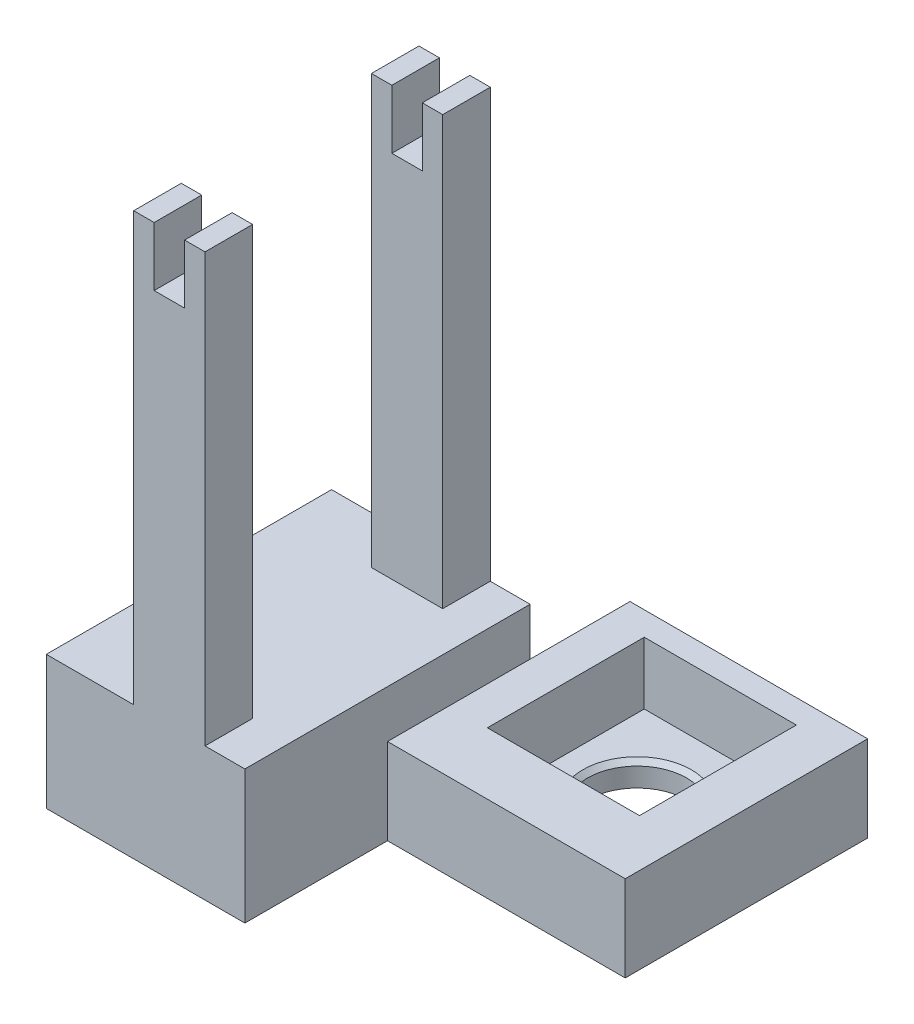
SolidWorks part; units mm, degrees
ref_plane "Front Plane" through (0, 0, 0) normal (0, 0, 1) x (1, 0, 0)
ref_plane "Top Plane" through (0, 0, 0) normal (0, 1, 0) x (1, 0, 0)
ref_plane "Right Plane" through (0, 0, 0) normal (1, 0, 0) x (0, 0, -1)
sketch "Sketch2" plane through (0, 0, 0) normal (0, 1, 0) x (1, 0, 0)
  line L1 (-25.885, -30) -> (15.885, -30)
  line L2 (-25.885, -30) -> (-25.885, 30)
  line L3 (-25.885, 30) -> (15.885, 30)
  line L4 (15.885, -30) -> (15.885, 30)
  point P0 (0, 0)
  point P6 (-25.885, 0)
  dimension "D1" = 41.77
  dimension "D2" = 60
  dimension "D3" = 25.885
extrude "Boss-Extrude1" add sketch "Sketch2" along normal blind 28.08
ref_plane "Plane1" [suppressed] through (0, 85, 0) normal (0, 1, 0) x (1, 0, 0)
sketch "Sketch3" [suppressed] plane through (0, 10, 0) normal (0, 1, 0) x (1, 0, 0)
  line L2 (-17.885, -27) -> (-17.885, -20)
  line L3 (-20.885, -20) -> (-17.885, -20)
  line L4 (-20.885, -30) -> (20.885, -30) construction
  line L5 (-17.885, -27) -> (-10.885, -27)
  line L6 (-20.885, -20) -> (-20.885, -30)
  line L7 (-10.885, -27) -> (-10.885, -30)
  line L8 (-20.885, -30) -> (-10.885, -30)
  line L9 (0, 30) -> (0, -30) construction
  line L10 (20.885, 30) -> (-20.885, 30) construction
  line L11 (-20.885, 0) -> (20.885, 0) construction
  line L12 (-20.885, 30) -> (-20.885, -30) construction
  line L13 (20.885, -30) -> (20.885, 30) construction
  line L14 (-17.885, -27) -> (-20.885, -27) construction
  line L15 (-17.885, -27) -> (-17.885, -30) construction
  line L16 (-20.885, 20) -> (-20.885, 30)
  line L17 (-20.885, 30) -> (-10.885, 30)
  line L18 (-10.885, 27) -> (-10.885, 30)
  line L19 (-17.885, 27) -> (-10.885, 27)
  line L20 (-17.885, 27) -> (-17.885, 20)
  line L21 (-20.885, 20) -> (-17.885, 20)
  line L22 (20.885, -20) -> (20.885, -30)
  line L23 (20.885, -30) -> (10.885, -30)
  line L24 (10.885, -27) -> (10.885, -30)
  line L25 (17.885, -27) -> (10.885, -27)
  line L26 (17.885, -27) -> (17.885, -20)
  line L27 (20.885, -20) -> (17.885, -20)
  line L28 (20.885, 20) -> (17.885, 20)
  line L29 (17.885, 27) -> (17.885, 20)
  line L30 (17.885, 27) -> (10.885, 27)
  line L31 (10.885, 27) -> (10.885, 30)
  line L32 (20.885, 30) -> (10.885, 30)
  line L33 (20.885, 20) -> (20.885, 30)
  dimension "D1" = 10
  dimension "D2" = 3
  dimension "D4" = 10
  dimension "D5" = 3
extrude "Boss-Extrude2" [suppressed] add sketch "Sketch3" along normal up to surface (75 mm away)
sketch "Sketch4" [suppressed] plane through (0, 0, 0) normal (0, -1, 0) x (1, 0, 0)
  line L0 (20.885, -30) -> (20.885, -5)
  line L1 (20.885, -30) -> (60.885, -30)
  line L2 (20.885, -5) -> (60.885, -5)
  line L3 (60.885, -30) -> (60.885, -5)
  line L4 (20.885, 30) -> (20.885, -30) construction
  dimension "D1" = 40
  dimension "D2" = 25
extrude "Boss-Extrude3" [suppressed] add sketch "Sketch4" against normal blind 10
sketch "Sketch6" plane through (0, 28.08, 0) normal (0, 1, 0) x (1, 0, 0)
  line L0 (-25.885, -30) -> (15.885, -30) construction
  line L1 (-7.5, -30) -> (7.5, -30)
  line L2 (-7.5, -30) -> (-7.5, -20)
  line L3 (-7.5, -20) -> (7.5, -20)
  line L4 (7.5, -30) -> (7.5, -20)
  line L5 (15.885, 30) -> (-25.885, 30) construction
  line L6 (-7.5, 30) -> (7.5, 30)
  line L7 (-7.5, 30) -> (-7.5, 20)
  line L8 (-7.5, 20) -> (7.5, 20)
  line L9 (7.5, 30) -> (7.5, 20)
  point P6 (0, -20)
  point P14 (0, 20)
  dimension "D1" = 10
  dimension "D2" = 15
extrude "Boss-Extrude4" add sketch "Sketch6" along normal blind 90
sketch "Sketch7" plane through (0, 0, -30) normal (0, 0, -1) x (-1, 0, 0)
  line L0 (-7.5, 118.08) -> (7.5, 118.08) construction
  line L1 (-3.2, 118.08) -> (3.2, 118.08)
  line L2 (-3.2, 118.08) -> (-3.2, 105.68)
  line L3 (-3.2, 105.68) -> (3.2, 105.68)
  line L4 (3.2, 118.08) -> (3.2, 105.68)
  point P6 (0, 105.68)
  dimension "D1" = 6.4
  dimension "D2" = 12.4
extrude "Cut-Extrude1" cut sketch "Sketch7" against normal through all
sketch "Sketch8" plane through (15.885, 0, 0) normal (1, 0, 0) x (0, 0, -1)
  line L0 (-30, 0) -> (30, 0) construction
  line L1 (51, 0) -> (0, 0)
  line L2 (51, 0) -> (51, 18.08)
  line L3 (51, 18.08) -> (0, 18.08)
  line L4 (0, 0) -> (0, 18.08)
  line L5 (30, 28.08) -> (30, 0) construction
  point P5 (0, 0)
  dimension "D1" = 18.08
  dimension "D2" = 51
  dimension "D3" = 30
extrude "Boss-Extrude5" add sketch "Sketch8" along normal blind 50
ref_plane "Plane2" through (55.885, 0, 0) normal (1, 0, 0) x (0, 0, -1)
sketch "Sketch9" plane through (55.885, 0, 0) normal (1, 0, 0) x (0, 0, -1)
  line L0 (0, 0) -> (51, 0) construction
  line L5 (46, 18.08) -> (13, 18.08)
  line L6 (46, 18.08) -> (46, 5)
  line L7 (46, 5) -> (13, 5)
  line L8 (13, 18.08) -> (13, 5)
  line L9 (51, 18.08) -> (0, 18.08) construction
  line L10 (51, 0) -> (51, 18.08) construction
  dimension "D1" = 5
  dimension "D2" = 33
  dimension "D3" = 5
extrude "Cut-Extrude2" cut sketch "Sketch9" against normal blind 32
sketch "Sketch10" plane through (0, 0, 0) normal (0, -1, 0) x (1, 0, 0)
  line L0 (12.885, 27) -> (12.885, -27)
  line L1 (-22.885, -27) -> (12.885, -27)
  line L2 (-22.885, 27) -> (-22.885, -27)
  line L3 (-22.885, 27) -> (12.885, 27)
  line L34 (15.885, -30) -> (-25.885, -30) construction
  line L35 (-25.885, 30) -> (15.885, 30) construction
  line L37 (-25.885, 30) -> (-25.885, -30) construction
  line L38 (-25.885, -30) -> (15.885, -30) construction
  line L39 (15.885, 30) -> (15.885, -30) construction
  line L40 (15.885, 30) -> (15.885, 0) construction
  dimension "D1" = 3
extrude "Cut-Extrude3" cut sketch "Sketch10" against normal blind 25.08
sketch "Sketch11" plane through (0, 0, 0) normal (0, -1, 0) x (1, 0, 0)
  line L5 (62.885, -12) -> (12.885, -12)
  line L6 (62.885, -12) -> (62.885, -3)
  line L7 (62.885, -3) -> (12.885, -3)
  line L8 (12.885, -12) -> (12.885, -3)
  line L9 (65.885, 0) -> (65.885, -51) construction
  line L10 (15.885, -30) -> (-25.885, -30) construction
  line L11 (65.885, 0) -> (15.885, 0) construction
  line L12 (12.885, -27) -> (12.885, 27) construction
  dimension "D1" = 3
  dimension "D2" = 18
  dimension "D3" = 3
extrude "Cut-Extrude4" cut sketch "Sketch11" against normal blind 15.08
sketch "Sketch12" plane through (65.885, 0, 0) normal (1, 0, 0) x (0, 0, -1)
  line L4 (46, 5) -> (46, 18.08)
  line L5 (46, 18.08) -> (13, 18.08)
  line L6 (13, 18.08) -> (13, 5)
  line L7 (13, 5) -> (46, 5)
  line L24 (46, 5) -> (46, 18.08)
  line L25 (46, 18.08) -> (13, 18.08)
  line L26 (13, 18.08) -> (13, 5)
  line L27 (13, 5) -> (46, 5)
  dimension "D1" = 0
sketch "Sketch13" plane through (0, 5, 0) normal (0, 1, 0) x (1, 0, 0)
  line L1 (23.885, 46) -> (55.885, 46) construction
  line L4 (55.885, -9.944) -> (55.885, 9.944) construction
  circle A0 centre (39.885, 28.5) radius 10.4
  dimension "D1" = 20.8
  dimension "D2" = 17.5
  dimension "D3" = 16
extrude "Cut-Extrude5" cut sketch "Sketch13" against normal blind 10
chamfer "Chamfer1" distance 1 angle 45 1 edges at (39.885, 5, -18.1)
